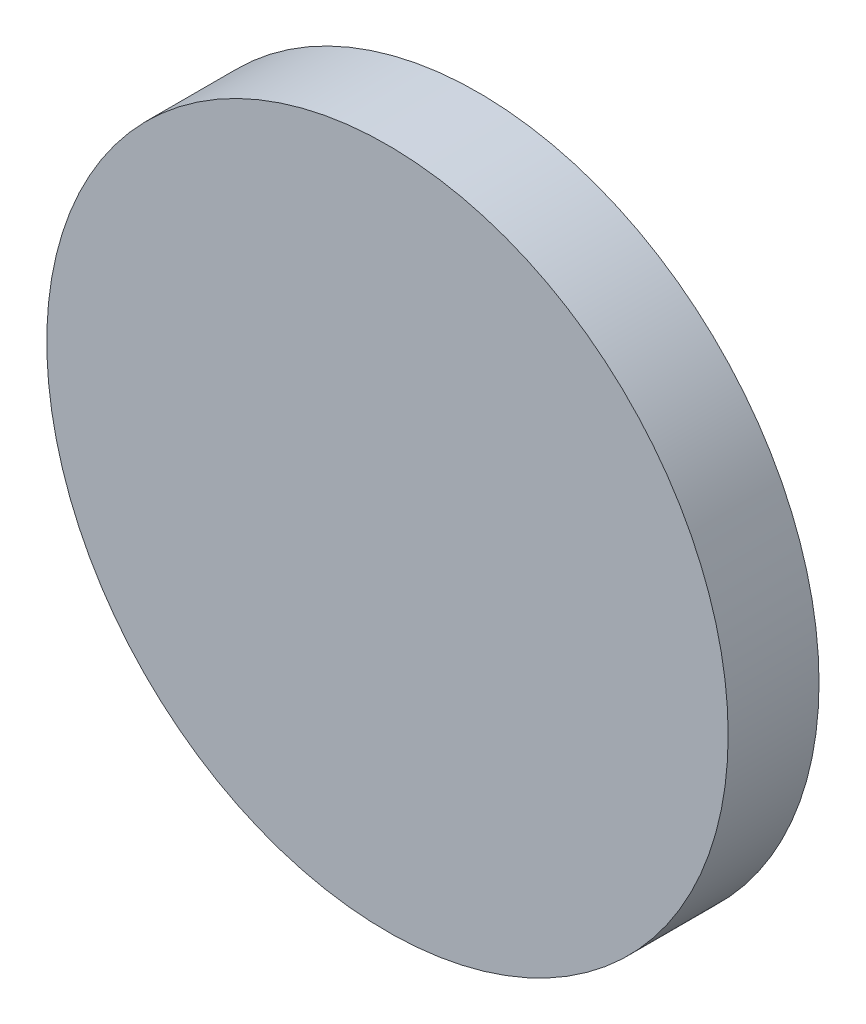
SolidWorks part; units mm, degrees
ref_plane "前视基准面" through (0, 0, 0) normal (0, 0, 1) x (1, 0, 0)
ref_plane "上视基准面" through (0, 0, 0) normal (0, 1, 0) x (1, 0, 0)
ref_plane "右视基准面" through (0, 0, 0) normal (1, 0, 0) x (0, 0, -1)
other "Configuration Table"
sketch "草图1" plane through (0, 0, 0) normal (0, 0, 1) x (1, 0, 0)
  circle A0 centre (0, 0) radius 3.5
  circle A1 centre (0, 0) radius 4.5
  dimension "D1" = 7
  dimension "D2" = 9
extrude "凸台-拉伸1" add sketch "草图1" along normal blind 2
sketch "草图2" plane through (0, 0, 2) normal (0, 0, 1) x (1, 0, 0)
  circle A0 centre (0, 0) radius 7.5
  circle A1 centre (0, 0) radius 4.5 construction
  dimension "D1" = 3
extrude "凸台-拉伸2" add sketch "草图2" along normal blind 2
